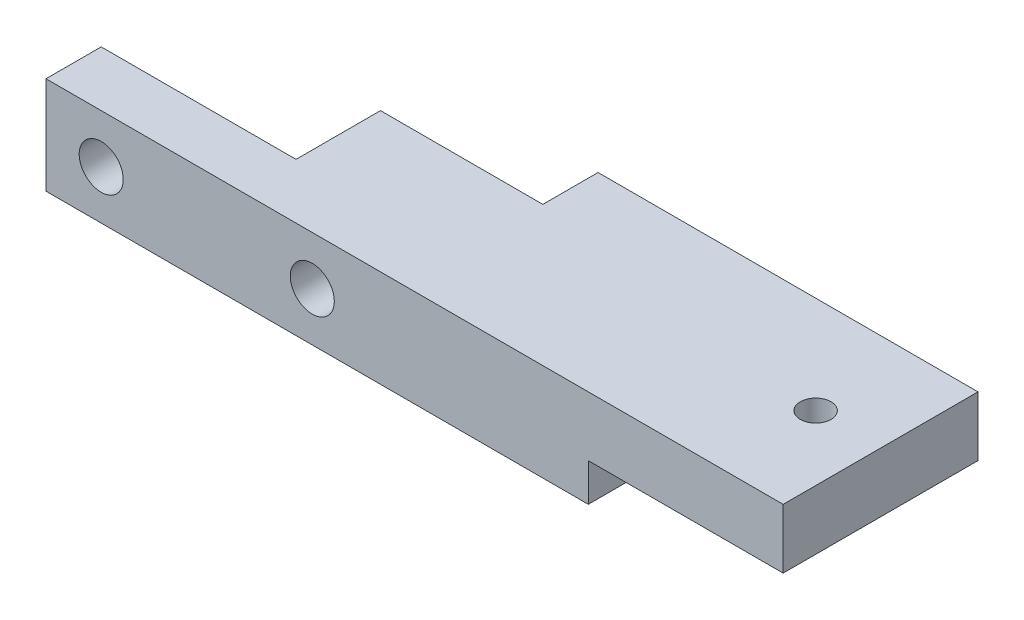
SolidWorks part; units mm, degrees
material "6061-T6 (SS)"
ref_plane "Front Plane" through (0, 0, 0) normal (0, 0, 1) x (1, 0, 0)
ref_plane "Top Plane" through (0, 0, 0) normal (0, 1, 0) x (1, 0, 0)
ref_plane "Right Plane" through (0, 0, 0) normal (1, 0, 0) x (0, 0, -1)
sketch "Sketch1" plane through (0, 0, 0) normal (0, 1, 0) x (1, 0, 0)
  line L0 (-14.9225, -4.1275) -> (-14.9225, -9.525)
  line L1 (20.0025, 4.1275) -> (4.1275, 4.1275)
  line L2 (0, 0) -> (50.8, 0) construction
  line L4 (-14.9225, -4.1275) -> (4.1275, -4.1275)
  line L5 (4.1275, 4.1275) -> (4.1275, -4.1275)
  line L8 (20.0025, 9.525) -> (57.15, 9.525)
  line L9 (20.0025, 9.525) -> (20.0025, 4.1275)
  line L10 (-14.9225, -9.525) -> (57.15, -9.525)
  line L11 (57.15, 9.525) -> (57.15, -9.525)
  circle A3 centre (50.8, 0) radius 1.5
  point P7 (4.1275, 0)
  dimension "D1" = 4.1275
  dimension "D2" = 50.8
  dimension "D3" = 8.255
  dimension "D4" = 3
  dimension "D5" = 19.05
  dimension "D6" = 19.05
  dimension "D7" = 15.875
  dimension "D8" = 6.35
extrude "Boss-Extrude1" add sketch "Sketch1" along normal mid plane 9.525
sketch "Sketch2" plane through (0, 0, 9.525) normal (0, 0, 1) x (1, 0, 0)
  line L0 (-4.1275, 0) -> (4.1275, 0) construction
  circle A0 centre (-9.525, 0) radius 2.1527
  circle A1 centre (11.1125, 0) radius 2.1527
  point P7 (0, 0)
  dimension "D1" = 4.3053
  dimension "D2" = 9.525
  dimension "D3" = 11.1125
  dimension "D4" = 8.255
extrude "Cut-Extrude1" cut sketch "Sketch2" against normal through all
sketch "Sketch3" plane through (0, -4.7625, 0) normal (0, -1, 0) x (1, 0, 0)
  line L0 (57.15, -9.525) -> (20.0025, -9.525) construction
  line L1 (57.15, 9.525) -> (38.1, 9.525)
  line L2 (57.15, 9.525) -> (57.15, -9.525)
  line L3 (57.15, -9.525) -> (38.1, -9.525)
  line L4 (38.1, 9.525) -> (38.1, -9.525)
  line L5 (57.15, 9.525) -> (38.1, -9.525) construction
  line L6 (57.15, -9.525) -> (38.1, 9.525) construction
  point P4 (47.625, 0)
  dimension "D1" = 19.05
extrude "Cut-Extrude2" cut sketch "Sketch3" against normal blind 3.7
